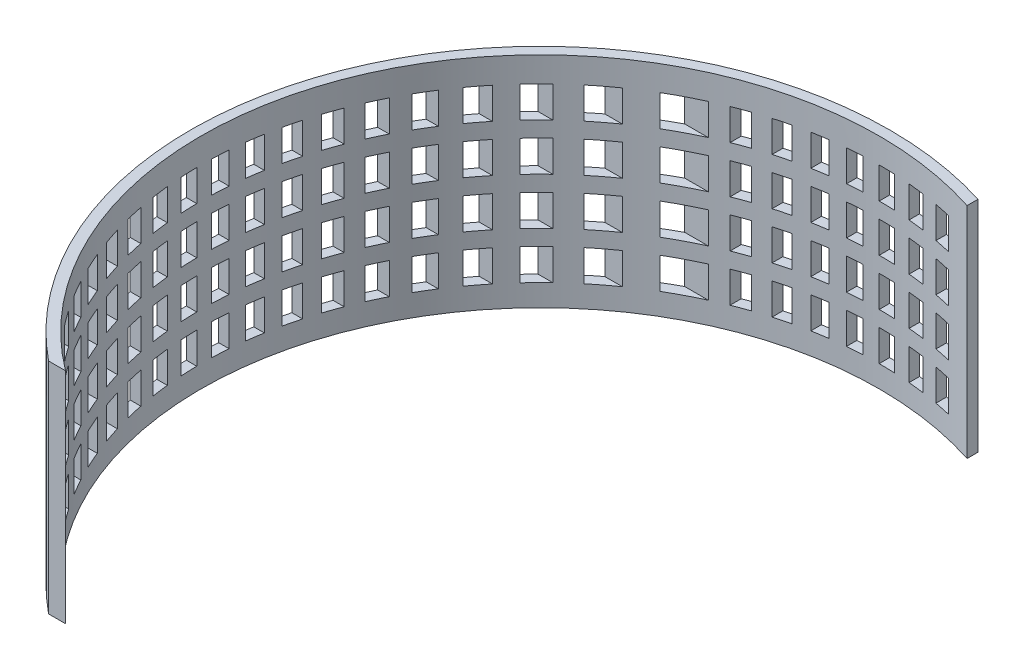
SolidWorks part; units mm, degrees
ref_plane "前视基准面" through (0, 0, 0) normal (0, 0, 1) x (1, 0, 0)
ref_plane "上视基准面" through (0, 0, 0) normal (0, 1, 0) x (1, 0, 0)
ref_plane "右视基准面" through (0, 0, 0) normal (1, 0, 0) x (0, 0, -1)
sketch "草图1" plane through (0, 0, 0) normal (0, 1, 0) x (1, 0, 0)
  line L0 (10, 31.9726) -> (10, 30.9233)
  line L3 (-19.5, -26) -> (-21.1246, -26)
  arc A0 (10, 30.9233) -> (-19.5, -26) centre (0, 0) ccw
  arc A1 (10, 31.9726) -> (-21.1246, -26) centre (0, 0) ccw
  circle A2 centre (0, 0) radius 33.5 construction
  circle A3 centre (0, 0) radius 32.5 construction
  dimension "D1" = 65
  dimension "D2" = 10
  dimension "D3" = 26
  dimension "D4" = 1
extrude "凸台-拉伸1" add sketch "草图1" along normal blind 21
sketch "草图2" plane through (0, 0, 0) normal (1, 0, 0) x (0, 0, -1)
  line L0 (-20.01, 18.5883) -> (-20.01, 15.5883)
  line L1 (-23.01, 18.5883) -> (-21.4184, 18.5883)
  line L2 (-23.01, 18.5883) -> (-23.01, 15.5883)
  line L3 (-23.01, 15.5883) -> (-21.4184, 15.5883)
  line L4 (-21.4184, 18.5883) -> (-21.4184, 15.5883)
  line L5 (-20.01, 18.5883) -> (-18.4184, 18.5883)
  line L6 (-18.4184, 18.5883) -> (-18.4184, 15.5883)
  line L7 (-20.01, 15.5883) -> (-18.4184, 15.5883)
  line L8 (-17.01, 18.5883) -> (-17.01, 15.5883)
  line L9 (-17.01, 18.5883) -> (-15.4184, 18.5883)
  line L10 (-15.4184, 18.5883) -> (-15.4184, 15.5883)
  line L11 (-17.01, 15.5883) -> (-15.4184, 15.5883)
  line L12 (-14.01, 18.5883) -> (-14.01, 15.5883)
  line L13 (-14.01, 18.5883) -> (-12.4184, 18.5883)
  line L14 (-12.4184, 18.5883) -> (-12.4184, 15.5883)
  line L15 (-14.01, 15.5883) -> (-12.4184, 15.5883)
  line L16 (-11.01, 18.5883) -> (-11.01, 15.5883)
  line L17 (-11.01, 18.5883) -> (-9.4184, 18.5883)
  line L18 (-9.4184, 18.5883) -> (-9.4184, 15.5883)
  line L19 (-11.01, 15.5883) -> (-9.4184, 15.5883)
  line L20 (-8.01, 18.5883) -> (-8.01, 15.5883)
  line L21 (-8.01, 18.5883) -> (-6.4184, 18.5883)
  line L22 (-6.4184, 18.5883) -> (-6.4184, 15.5883)
  line L23 (-8.01, 15.5883) -> (-6.4184, 15.5883)
  line L24 (-5.01, 18.5883) -> (-5.01, 15.5883)
  line L25 (-5.01, 18.5883) -> (-3.4184, 18.5883)
  line L26 (-3.4184, 18.5883) -> (-3.4184, 15.5883)
  line L27 (-5.01, 15.5883) -> (-3.4184, 15.5883)
  line L28 (-2.01, 18.5883) -> (-2.01, 15.5883)
  line L29 (-2.01, 18.5883) -> (-0.4184, 18.5883)
  line L30 (-0.4184, 18.5883) -> (-0.4184, 15.5883)
  line L31 (-2.01, 15.5883) -> (-0.4184, 15.5883)
  line L32 (0.99, 18.5883) -> (0.99, 15.5883)
  line L33 (0.99, 18.5883) -> (2.5816, 18.5883)
  line L34 (2.5816, 18.5883) -> (2.5816, 15.5883)
  line L35 (0.99, 15.5883) -> (2.5816, 15.5883)
  line L36 (3.99, 18.5883) -> (3.99, 15.5883)
  line L37 (3.99, 18.5883) -> (5.5816, 18.5883)
  line L38 (5.5816, 18.5883) -> (5.5816, 15.5883)
  line L39 (3.99, 15.5883) -> (5.5816, 15.5883)
  line L40 (6.99, 18.5883) -> (6.99, 15.5883)
  line L41 (6.99, 18.5883) -> (8.5816, 18.5883)
  line L42 (8.5816, 18.5883) -> (8.5816, 15.5883)
  line L43 (6.99, 15.5883) -> (8.5816, 15.5883)
  line L44 (9.99, 18.5883) -> (9.99, 15.5883)
  line L45 (9.99, 18.5883) -> (11.5816, 18.5883)
  line L46 (11.5816, 18.5883) -> (11.5816, 15.5883)
  line L47 (9.99, 15.5883) -> (11.5816, 15.5883)
  line L48 (12.99, 18.5883) -> (12.99, 15.5883)
  line L49 (12.99, 18.5883) -> (14.5816, 18.5883)
  line L50 (14.5816, 18.5883) -> (14.5816, 15.5883)
  line L51 (12.99, 15.5883) -> (14.5816, 15.5883)
  line L52 (15.99, 18.5883) -> (15.99, 15.5883)
  line L53 (15.99, 18.5883) -> (17.5816, 18.5883)
  line L54 (17.5816, 18.5883) -> (17.5816, 15.5883)
  line L55 (15.99, 15.5883) -> (17.5816, 15.5883)
  line L56 (18.99, 18.5883) -> (18.99, 15.5883)
  line L57 (18.99, 18.5883) -> (20.5816, 18.5883)
  line L58 (20.5816, 18.5883) -> (20.5816, 15.5883)
  line L59 (18.99, 15.5883) -> (20.5816, 15.5883)
  line L60 (21.99, 18.5883) -> (21.99, 15.5883)
  line L61 (21.99, 18.5883) -> (23.5816, 18.5883)
  line L62 (23.5816, 18.5883) -> (23.5816, 15.5883)
  line L63 (21.99, 15.5883) -> (23.5816, 15.5883)
  line L64 (24.99, 18.5883) -> (24.99, 15.5883)
  line L65 (24.99, 18.5883) -> (26.5816, 18.5883)
  line L66 (26.5816, 18.5883) -> (26.5816, 15.5883)
  line L67 (24.99, 15.5883) -> (26.5816, 15.5883)
  line L68 (27.99, 18.5883) -> (27.99, 15.5883)
  line L69 (27.99, 18.5883) -> (29.5816, 18.5883)
  line L70 (29.5816, 18.5883) -> (29.5816, 15.5883)
  line L71 (27.99, 15.5883) -> (29.5816, 15.5883)
  line L72 (27.99, 14.0883) -> (27.99, 11.0883)
  line L73 (27.99, 11.0883) -> (29.5816, 11.0883)
  line L74 (29.5816, 14.0883) -> (29.5816, 11.0883)
  line L75 (27.99, 14.0883) -> (29.5816, 14.0883)
  line L76 (24.99, 14.0883) -> (24.99, 11.0883)
  line L77 (24.99, 11.0883) -> (26.5816, 11.0883)
  line L78 (26.5816, 14.0883) -> (26.5816, 11.0883)
  line L79 (24.99, 14.0883) -> (26.5816, 14.0883)
  line L80 (21.99, 14.0883) -> (21.99, 11.0883)
  line L81 (21.99, 11.0883) -> (23.5816, 11.0883)
  line L82 (23.5816, 14.0883) -> (23.5816, 11.0883)
  line L83 (21.99, 14.0883) -> (23.5816, 14.0883)
  line L84 (18.99, 14.0883) -> (18.99, 11.0883)
  line L85 (18.99, 11.0883) -> (20.5816, 11.0883)
  line L86 (20.5816, 14.0883) -> (20.5816, 11.0883)
  line L87 (18.99, 14.0883) -> (20.5816, 14.0883)
  line L88 (15.99, 14.0883) -> (15.99, 11.0883)
  line L89 (15.99, 11.0883) -> (17.5816, 11.0883)
  line L90 (17.5816, 14.0883) -> (17.5816, 11.0883)
  line L91 (15.99, 14.0883) -> (17.5816, 14.0883)
  line L92 (12.99, 14.0883) -> (12.99, 11.0883)
  line L93 (12.99, 11.0883) -> (14.5816, 11.0883)
  line L94 (14.5816, 14.0883) -> (14.5816, 11.0883)
  line L95 (12.99, 14.0883) -> (14.5816, 14.0883)
  line L96 (9.99, 14.0883) -> (9.99, 11.0883)
  line L97 (9.99, 11.0883) -> (11.5816, 11.0883)
  line L98 (11.5816, 14.0883) -> (11.5816, 11.0883)
  line L99 (9.99, 14.0883) -> (11.5816, 14.0883)
  line L100 (6.99, 14.0883) -> (6.99, 11.0883)
  line L101 (6.99, 11.0883) -> (8.5816, 11.0883)
  line L102 (8.5816, 14.0883) -> (8.5816, 11.0883)
  line L103 (6.99, 14.0883) -> (8.5816, 14.0883)
  line L104 (3.99, 14.0883) -> (3.99, 11.0883)
  line L105 (3.99, 11.0883) -> (5.5816, 11.0883)
  line L106 (5.5816, 14.0883) -> (5.5816, 11.0883)
  line L107 (3.99, 14.0883) -> (5.5816, 14.0883)
  line L108 (0.99, 14.0883) -> (0.99, 11.0883)
  line L109 (0.99, 11.0883) -> (2.5816, 11.0883)
  line L110 (2.5816, 14.0883) -> (2.5816, 11.0883)
  line L111 (0.99, 14.0883) -> (2.5816, 14.0883)
  line L112 (-2.01, 14.0883) -> (-2.01, 11.0883)
  line L113 (-2.01, 11.0883) -> (-0.4184, 11.0883)
  line L114 (-0.4184, 14.0883) -> (-0.4184, 11.0883)
  line L115 (-2.01, 14.0883) -> (-0.4184, 14.0883)
  line L116 (-5.01, 14.0883) -> (-5.01, 11.0883)
  line L117 (-5.01, 11.0883) -> (-3.4184, 11.0883)
  line L118 (-3.4184, 14.0883) -> (-3.4184, 11.0883)
  line L119 (-5.01, 14.0883) -> (-3.4184, 14.0883)
  line L120 (-8.01, 14.0883) -> (-8.01, 11.0883)
  line L121 (-8.01, 11.0883) -> (-6.4184, 11.0883)
  line L122 (-6.4184, 14.0883) -> (-6.4184, 11.0883)
  line L123 (-8.01, 14.0883) -> (-6.4184, 14.0883)
  line L124 (-11.01, 14.0883) -> (-11.01, 11.0883)
  line L125 (-11.01, 11.0883) -> (-9.4184, 11.0883)
  line L126 (-9.4184, 14.0883) -> (-9.4184, 11.0883)
  line L127 (-11.01, 14.0883) -> (-9.4184, 14.0883)
  line L128 (-14.01, 14.0883) -> (-14.01, 11.0883)
  line L129 (-14.01, 11.0883) -> (-12.4184, 11.0883)
  line L130 (-12.4184, 14.0883) -> (-12.4184, 11.0883)
  line L131 (-14.01, 14.0883) -> (-12.4184, 14.0883)
  line L132 (-17.01, 14.0883) -> (-17.01, 11.0883)
  line L133 (-17.01, 11.0883) -> (-15.4184, 11.0883)
  line L134 (-15.4184, 14.0883) -> (-15.4184, 11.0883)
  line L135 (-17.01, 14.0883) -> (-15.4184, 14.0883)
  line L136 (-20.01, 14.0883) -> (-20.01, 11.0883)
  line L137 (-20.01, 11.0883) -> (-18.4184, 11.0883)
  line L138 (-18.4184, 14.0883) -> (-18.4184, 11.0883)
  line L139 (-20.01, 14.0883) -> (-18.4184, 14.0883)
  line L140 (-23.01, 14.0883) -> (-23.01, 11.0883)
  line L141 (-23.01, 14.0883) -> (-21.4184, 14.0883)
  line L142 (-21.4184, 14.0883) -> (-21.4184, 11.0883)
  line L143 (-23.01, 11.0883) -> (-21.4184, 11.0883)
  line L144 (27.99, 9.5883) -> (27.99, 6.5883)
  line L145 (27.99, 6.5883) -> (29.5816, 6.5883)
  line L146 (29.5816, 9.5883) -> (29.5816, 6.5883)
  line L147 (27.99, 9.5883) -> (29.5816, 9.5883)
  line L148 (24.99, 9.5883) -> (24.99, 6.5883)
  line L149 (24.99, 6.5883) -> (26.5816, 6.5883)
  line L150 (26.5816, 9.5883) -> (26.5816, 6.5883)
  line L151 (24.99, 9.5883) -> (26.5816, 9.5883)
  line L152 (21.99, 9.5883) -> (21.99, 6.5883)
  line L153 (21.99, 6.5883) -> (23.5816, 6.5883)
  line L154 (23.5816, 9.5883) -> (23.5816, 6.5883)
  line L155 (21.99, 9.5883) -> (23.5816, 9.5883)
  line L156 (18.99, 9.5883) -> (18.99, 6.5883)
  line L157 (18.99, 6.5883) -> (20.5816, 6.5883)
  line L158 (20.5816, 9.5883) -> (20.5816, 6.5883)
  line L159 (18.99, 9.5883) -> (20.5816, 9.5883)
  line L160 (15.99, 9.5883) -> (15.99, 6.5883)
  line L161 (15.99, 6.5883) -> (17.5816, 6.5883)
  line L162 (17.5816, 9.5883) -> (17.5816, 6.5883)
  line L163 (15.99, 9.5883) -> (17.5816, 9.5883)
  line L164 (12.99, 9.5883) -> (12.99, 6.5883)
  line L165 (12.99, 6.5883) -> (14.5816, 6.5883)
  line L166 (14.5816, 9.5883) -> (14.5816, 6.5883)
  line L167 (12.99, 9.5883) -> (14.5816, 9.5883)
  line L168 (9.99, 9.5883) -> (9.99, 6.5883)
  line L169 (9.99, 6.5883) -> (11.5816, 6.5883)
  line L170 (11.5816, 9.5883) -> (11.5816, 6.5883)
  line L171 (9.99, 9.5883) -> (11.5816, 9.5883)
  line L172 (6.99, 9.5883) -> (6.99, 6.5883)
  line L173 (6.99, 6.5883) -> (8.5816, 6.5883)
  line L174 (8.5816, 9.5883) -> (8.5816, 6.5883)
  line L175 (6.99, 9.5883) -> (8.5816, 9.5883)
  line L176 (3.99, 9.5883) -> (3.99, 6.5883)
  line L177 (3.99, 6.5883) -> (5.5816, 6.5883)
  line L178 (5.5816, 9.5883) -> (5.5816, 6.5883)
  line L179 (3.99, 9.5883) -> (5.5816, 9.5883)
  line L180 (0.99, 9.5883) -> (0.99, 6.5883)
  line L181 (0.99, 6.5883) -> (2.5816, 6.5883)
  line L182 (2.5816, 9.5883) -> (2.5816, 6.5883)
  line L183 (0.99, 9.5883) -> (2.5816, 9.5883)
  line L184 (-2.01, 9.5883) -> (-2.01, 6.5883)
  line L185 (-2.01, 6.5883) -> (-0.4184, 6.5883)
  line L186 (-0.4184, 9.5883) -> (-0.4184, 6.5883)
  line L187 (-2.01, 9.5883) -> (-0.4184, 9.5883)
  line L188 (-5.01, 9.5883) -> (-5.01, 6.5883)
  line L189 (-5.01, 6.5883) -> (-3.4184, 6.5883)
  line L190 (-3.4184, 9.5883) -> (-3.4184, 6.5883)
  line L191 (-5.01, 9.5883) -> (-3.4184, 9.5883)
  line L192 (-8.01, 9.5883) -> (-8.01, 6.5883)
  line L193 (-8.01, 6.5883) -> (-6.4184, 6.5883)
  line L194 (-6.4184, 9.5883) -> (-6.4184, 6.5883)
  line L195 (-8.01, 9.5883) -> (-6.4184, 9.5883)
  line L196 (-11.01, 9.5883) -> (-11.01, 6.5883)
  line L197 (-11.01, 6.5883) -> (-9.4184, 6.5883)
  line L198 (-9.4184, 9.5883) -> (-9.4184, 6.5883)
  line L199 (-11.01, 9.5883) -> (-9.4184, 9.5883)
  line L200 (-14.01, 9.5883) -> (-14.01, 6.5883)
  line L201 (-14.01, 6.5883) -> (-12.4184, 6.5883)
  line L202 (-12.4184, 9.5883) -> (-12.4184, 6.5883)
  line L203 (-14.01, 9.5883) -> (-12.4184, 9.5883)
  line L204 (-17.01, 9.5883) -> (-17.01, 6.5883)
  line L205 (-17.01, 6.5883) -> (-15.4184, 6.5883)
  line L206 (-15.4184, 9.5883) -> (-15.4184, 6.5883)
  line L207 (-17.01, 9.5883) -> (-15.4184, 9.5883)
  line L208 (-20.01, 9.5883) -> (-20.01, 6.5883)
  line L209 (-20.01, 6.5883) -> (-18.4184, 6.5883)
  line L210 (-18.4184, 9.5883) -> (-18.4184, 6.5883)
  line L211 (-20.01, 9.5883) -> (-18.4184, 9.5883)
  line L212 (-23.01, 9.5883) -> (-23.01, 6.5883)
  line L213 (-23.01, 9.5883) -> (-21.4184, 9.5883)
  line L214 (-21.4184, 9.5883) -> (-21.4184, 6.5883)
  line L215 (-23.01, 6.5883) -> (-21.4184, 6.5883)
  line L216 (27.99, 5.0883) -> (27.99, 2.0883)
  line L217 (27.99, 2.0883) -> (29.5816, 2.0883)
  line L218 (29.5816, 5.0883) -> (29.5816, 2.0883)
  line L219 (27.99, 5.0883) -> (29.5816, 5.0883)
  line L220 (24.99, 5.0883) -> (24.99, 2.0883)
  line L221 (24.99, 2.0883) -> (26.5816, 2.0883)
  line L222 (26.5816, 5.0883) -> (26.5816, 2.0883)
  line L223 (24.99, 5.0883) -> (26.5816, 5.0883)
  line L224 (21.99, 5.0883) -> (21.99, 2.0883)
  line L225 (21.99, 2.0883) -> (23.5816, 2.0883)
  line L226 (23.5816, 5.0883) -> (23.5816, 2.0883)
  line L227 (21.99, 5.0883) -> (23.5816, 5.0883)
  line L228 (18.99, 5.0883) -> (18.99, 2.0883)
  line L229 (18.99, 2.0883) -> (20.5816, 2.0883)
  line L230 (20.5816, 5.0883) -> (20.5816, 2.0883)
  line L231 (18.99, 5.0883) -> (20.5816, 5.0883)
  line L232 (15.99, 5.0883) -> (15.99, 2.0883)
  line L233 (15.99, 2.0883) -> (17.5816, 2.0883)
  line L234 (17.5816, 5.0883) -> (17.5816, 2.0883)
  line L235 (15.99, 5.0883) -> (17.5816, 5.0883)
  line L236 (12.99, 5.0883) -> (12.99, 2.0883)
  line L237 (12.99, 2.0883) -> (14.5816, 2.0883)
  line L238 (14.5816, 5.0883) -> (14.5816, 2.0883)
  line L239 (12.99, 5.0883) -> (14.5816, 5.0883)
  line L240 (9.99, 5.0883) -> (9.99, 2.0883)
  line L241 (9.99, 2.0883) -> (11.5816, 2.0883)
  line L242 (11.5816, 5.0883) -> (11.5816, 2.0883)
  line L243 (9.99, 5.0883) -> (11.5816, 5.0883)
  line L244 (6.99, 5.0883) -> (6.99, 2.0883)
  line L245 (6.99, 2.0883) -> (8.5816, 2.0883)
  line L246 (8.5816, 5.0883) -> (8.5816, 2.0883)
  line L247 (6.99, 5.0883) -> (8.5816, 5.0883)
  line L248 (3.99, 5.0883) -> (3.99, 2.0883)
  line L249 (3.99, 2.0883) -> (5.5816, 2.0883)
  line L250 (5.5816, 5.0883) -> (5.5816, 2.0883)
  line L251 (3.99, 5.0883) -> (5.5816, 5.0883)
  line L252 (0.99, 5.0883) -> (0.99, 2.0883)
  line L253 (0.99, 2.0883) -> (2.5816, 2.0883)
  line L254 (2.5816, 5.0883) -> (2.5816, 2.0883)
  line L255 (0.99, 5.0883) -> (2.5816, 5.0883)
  line L256 (-2.01, 5.0883) -> (-2.01, 2.0883)
  line L257 (-2.01, 2.0883) -> (-0.4184, 2.0883)
  line L258 (-0.4184, 5.0883) -> (-0.4184, 2.0883)
  line L259 (-2.01, 5.0883) -> (-0.4184, 5.0883)
  line L260 (-5.01, 5.0883) -> (-5.01, 2.0883)
  line L261 (-5.01, 2.0883) -> (-3.4184, 2.0883)
  line L262 (-3.4184, 5.0883) -> (-3.4184, 2.0883)
  line L263 (-5.01, 5.0883) -> (-3.4184, 5.0883)
  line L264 (-8.01, 5.0883) -> (-8.01, 2.0883)
  line L265 (-8.01, 2.0883) -> (-6.4184, 2.0883)
  line L266 (-6.4184, 5.0883) -> (-6.4184, 2.0883)
  line L267 (-8.01, 5.0883) -> (-6.4184, 5.0883)
  line L268 (-11.01, 5.0883) -> (-11.01, 2.0883)
  line L269 (-11.01, 2.0883) -> (-9.4184, 2.0883)
  line L270 (-9.4184, 5.0883) -> (-9.4184, 2.0883)
  line L271 (-11.01, 5.0883) -> (-9.4184, 5.0883)
  line L272 (-14.01, 5.0883) -> (-14.01, 2.0883)
  line L273 (-14.01, 2.0883) -> (-12.4184, 2.0883)
  line L274 (-12.4184, 5.0883) -> (-12.4184, 2.0883)
  line L275 (-14.01, 5.0883) -> (-12.4184, 5.0883)
  line L276 (-17.01, 5.0883) -> (-17.01, 2.0883)
  line L277 (-17.01, 2.0883) -> (-15.4184, 2.0883)
  line L278 (-15.4184, 5.0883) -> (-15.4184, 2.0883)
  line L279 (-17.01, 5.0883) -> (-15.4184, 5.0883)
  line L280 (-20.01, 5.0883) -> (-20.01, 2.0883)
  line L281 (-20.01, 2.0883) -> (-18.4184, 2.0883)
  line L282 (-18.4184, 5.0883) -> (-18.4184, 2.0883)
  line L283 (-20.01, 5.0883) -> (-18.4184, 5.0883)
  line L284 (-23.01, 5.0883) -> (-23.01, 2.0883)
  line L285 (-23.01, 5.0883) -> (-21.4184, 5.0883)
  line L286 (-21.4184, 5.0883) -> (-21.4184, 2.0883)
  line L287 (-23.01, 2.0883) -> (-21.4184, 2.0883)
  dimension "D1" = 1.5916
  dimension "D2" = 3
  dimension "D3" = 18
  dimension "D4" = 4
extrude "切除-拉伸1" cut sketch "草图2" against normal through all
sketch "草图3" plane through (0, 0, 0) normal (0, 0, 1) x (1, 0, 0)
  line L0 (-15.722, 18.5883) -> (-13.4603, 18.5883) construction
  line L1 (6, 18.5883) -> (7.5, 18.5883)
  line L2 (6, 18.5883) -> (6, 15.5883)
  line L3 (6, 15.5883) -> (7.5, 15.5883)
  line L4 (7.5, 18.5883) -> (7.5, 15.5883)
  line L5 (10, 21) -> (10, 0) construction
  line L6 (3, 18.5883) -> (3, 15.5883)
  line L7 (3, 18.5883) -> (4.5, 18.5883)
  line L8 (4.5, 18.5883) -> (4.5, 15.5883)
  line L9 (3, 15.5883) -> (4.5, 15.5883)
  line L10 (0, 18.5883) -> (0, 15.5883)
  line L11 (0, 18.5883) -> (1.5, 18.5883)
  line L12 (1.5, 18.5883) -> (1.5, 15.5883)
  line L13 (0, 15.5883) -> (1.5, 15.5883)
  line L14 (-3, 18.5883) -> (-3, 15.5883)
  line L15 (-3, 18.5883) -> (-1.5, 18.5883)
  line L16 (-1.5, 18.5883) -> (-1.5, 15.5883)
  line L17 (-3, 15.5883) -> (-1.5, 15.5883)
  line L18 (-6, 18.5883) -> (-6, 15.5883)
  line L19 (-6, 18.5883) -> (-4.5, 18.5883)
  line L20 (-4.5, 18.5883) -> (-4.5, 15.5883)
  line L21 (-6, 15.5883) -> (-4.5, 15.5883)
  line L22 (-9, 18.5883) -> (-9, 15.5883)
  line L23 (-9, 18.5883) -> (-7.5, 18.5883)
  line L24 (-7.5, 18.5883) -> (-7.5, 15.5883)
  line L25 (-9, 15.5883) -> (-7.5, 15.5883)
  line L26 (-12, 18.5883) -> (-12, 15.5883)
  line L27 (-12, 18.5883) -> (-10.5, 18.5883)
  line L28 (-10.5, 18.5883) -> (-10.5, 15.5883)
  line L29 (-12, 15.5883) -> (-10.5, 15.5883)
  line L30 (6, 14.0883) -> (6, 11.0883)
  line L31 (6, 14.0883) -> (7.5, 14.0883)
  line L32 (7.5, 14.0883) -> (7.5, 11.0883)
  line L33 (6, 11.0883) -> (7.5, 11.0883)
  line L34 (-12, 14.0883) -> (-12, 11.0883)
  line L35 (-12, 11.0883) -> (-10.5, 11.0883)
  line L36 (-10.5, 14.0883) -> (-10.5, 11.0883)
  line L37 (-12, 14.0883) -> (-10.5, 14.0883)
  line L38 (-9, 14.0883) -> (-9, 11.0883)
  line L39 (-9, 11.0883) -> (-7.5, 11.0883)
  line L40 (-7.5, 14.0883) -> (-7.5, 11.0883)
  line L41 (-9, 14.0883) -> (-7.5, 14.0883)
  line L42 (-6, 14.0883) -> (-6, 11.0883)
  line L43 (-6, 11.0883) -> (-4.5, 11.0883)
  line L44 (-4.5, 14.0883) -> (-4.5, 11.0883)
  line L45 (-6, 14.0883) -> (-4.5, 14.0883)
  line L46 (-3, 14.0883) -> (-3, 11.0883)
  line L47 (-3, 11.0883) -> (-1.5, 11.0883)
  line L48 (-1.5, 14.0883) -> (-1.5, 11.0883)
  line L49 (-3, 14.0883) -> (-1.5, 14.0883)
  line L50 (0, 14.0883) -> (0, 11.0883)
  line L51 (0, 11.0883) -> (1.5, 11.0883)
  line L52 (1.5, 14.0883) -> (1.5, 11.0883)
  line L53 (0, 14.0883) -> (1.5, 14.0883)
  line L54 (3, 14.0883) -> (3, 11.0883)
  line L55 (3, 11.0883) -> (4.5, 11.0883)
  line L56 (4.5, 14.0883) -> (4.5, 11.0883)
  line L57 (3, 14.0883) -> (4.5, 14.0883)
  line L58 (6, 9.5883) -> (6, 6.5883)
  line L59 (6, 9.5883) -> (7.5, 9.5883)
  line L60 (7.5, 9.5883) -> (7.5, 6.5883)
  line L61 (6, 6.5883) -> (7.5, 6.5883)
  line L62 (-12, 9.5883) -> (-12, 6.5883)
  line L63 (-12, 6.5883) -> (-10.5, 6.5883)
  line L64 (-10.5, 9.5883) -> (-10.5, 6.5883)
  line L65 (-12, 9.5883) -> (-10.5, 9.5883)
  line L66 (-9, 9.5883) -> (-9, 6.5883)
  line L67 (-9, 6.5883) -> (-7.5, 6.5883)
  line L68 (-7.5, 9.5883) -> (-7.5, 6.5883)
  line L69 (-9, 9.5883) -> (-7.5, 9.5883)
  line L70 (-6, 9.5883) -> (-6, 6.5883)
  line L71 (-6, 6.5883) -> (-4.5, 6.5883)
  line L72 (-4.5, 9.5883) -> (-4.5, 6.5883)
  line L73 (-6, 9.5883) -> (-4.5, 9.5883)
  line L74 (-3, 9.5883) -> (-3, 6.5883)
  line L75 (-3, 6.5883) -> (-1.5, 6.5883)
  line L76 (-1.5, 9.5883) -> (-1.5, 6.5883)
  line L77 (-3, 9.5883) -> (-1.5, 9.5883)
  line L78 (0, 9.5883) -> (0, 6.5883)
  line L79 (0, 6.5883) -> (1.5, 6.5883)
  line L80 (1.5, 9.5883) -> (1.5, 6.5883)
  line L81 (0, 9.5883) -> (1.5, 9.5883)
  line L82 (3, 9.5883) -> (3, 6.5883)
  line L83 (3, 6.5883) -> (4.5, 6.5883)
  line L84 (4.5, 9.5883) -> (4.5, 6.5883)
  line L85 (3, 9.5883) -> (4.5, 9.5883)
  line L86 (6, 5.0883) -> (6, 2.0883)
  line L87 (6, 5.0883) -> (7.5, 5.0883)
  line L88 (7.5, 5.0883) -> (7.5, 2.0883)
  line L89 (6, 2.0883) -> (7.5, 2.0883)
  line L90 (-12, 5.0883) -> (-12, 2.0883)
  line L91 (-12, 2.0883) -> (-10.5, 2.0883)
  line L92 (-10.5, 5.0883) -> (-10.5, 2.0883)
  line L93 (-12, 5.0883) -> (-10.5, 5.0883)
  line L94 (-9, 5.0883) -> (-9, 2.0883)
  line L95 (-9, 2.0883) -> (-7.5, 2.0883)
  line L96 (-7.5, 5.0883) -> (-7.5, 2.0883)
  line L97 (-9, 5.0883) -> (-7.5, 5.0883)
  line L98 (-6, 5.0883) -> (-6, 2.0883)
  line L99 (-6, 2.0883) -> (-4.5, 2.0883)
  line L100 (-4.5, 5.0883) -> (-4.5, 2.0883)
  line L101 (-6, 5.0883) -> (-4.5, 5.0883)
  line L102 (-3, 5.0883) -> (-3, 2.0883)
  line L103 (-3, 2.0883) -> (-1.5, 2.0883)
  line L104 (-1.5, 5.0883) -> (-1.5, 2.0883)
  line L105 (-3, 5.0883) -> (-1.5, 5.0883)
  line L106 (0, 5.0883) -> (0, 2.0883)
  line L107 (0, 2.0883) -> (1.5, 2.0883)
  line L108 (1.5, 5.0883) -> (1.5, 2.0883)
  line L109 (0, 5.0883) -> (1.5, 5.0883)
  line L110 (3, 5.0883) -> (3, 2.0883)
  line L111 (3, 2.0883) -> (4.5, 2.0883)
  line L112 (4.5, 5.0883) -> (4.5, 2.0883)
  line L113 (3, 5.0883) -> (4.5, 5.0883)
  dimension "D1" = 3
  dimension "D2" = 1.5
  dimension "D3" = 2.5
  dimension "D4" = 7
  dimension "D5" = 4
extrude "切除-拉伸2" cut sketch "草图3" against normal through all
